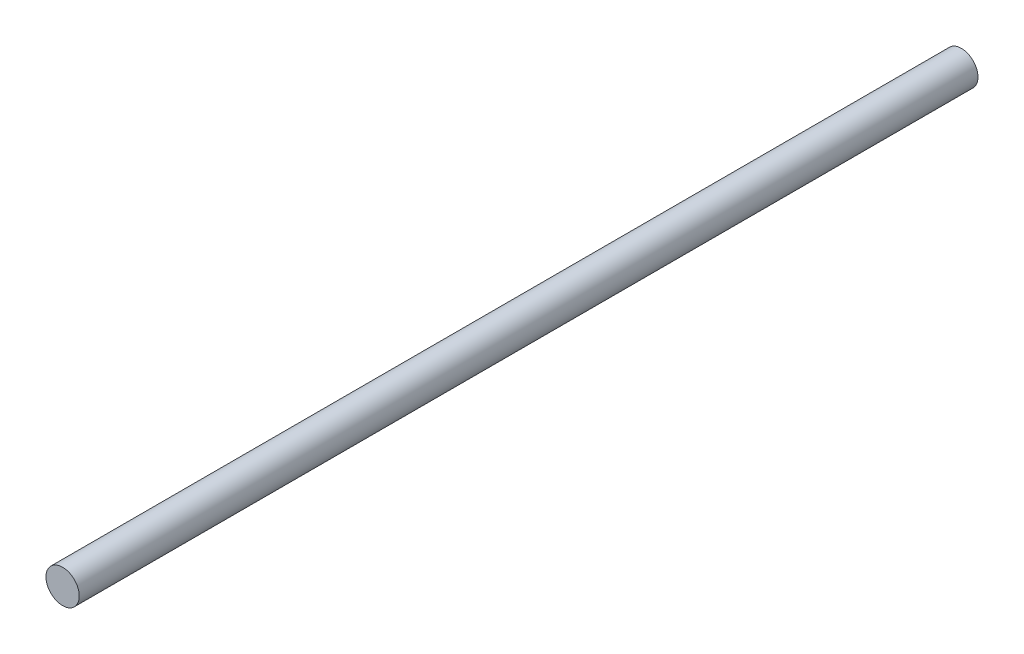
SolidWorks part; units mm, degrees
material "Plain Carbon Steel"
ref_plane "Front Plane" through (0, 0, 0) normal (0, 0, 1) x (1, 0, 0)
ref_plane "Top Plane" through (0, 0, 0) normal (0, 1, 0) x (1, 0, 0)
ref_plane "Right Plane" through (0, 0, 0) normal (1, 0, 0) x (0, 0, -1)
sketch "Sketch1" plane through (0, 0, 0) normal (0, 0, 1) x (1, 0, 0)
  circle A0 centre (0, 0) radius 1.5
  dimension "D1" = 3
extrude "Boss-Extrude1" add sketch "Sketch1" along normal blind 81
